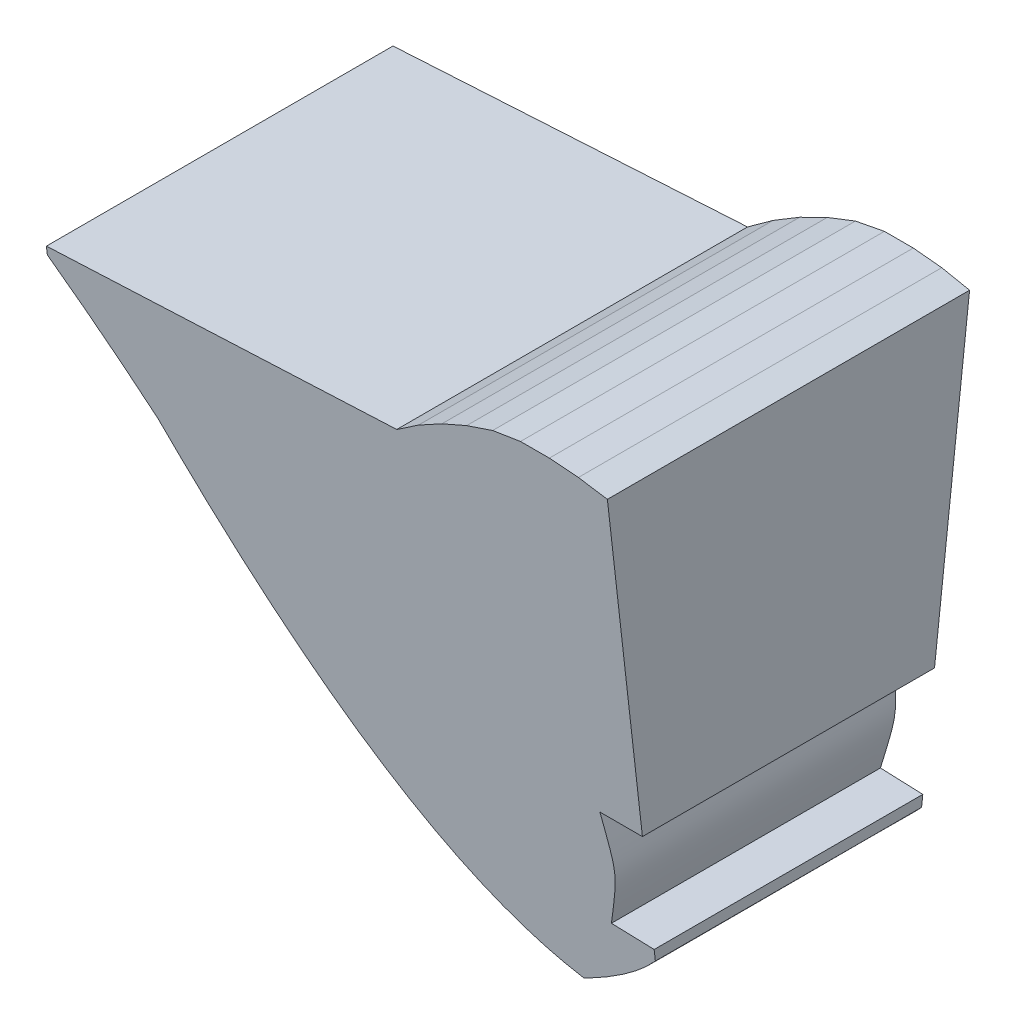
SolidWorks part; units mm, degrees
ref_plane "Alzado" through (0, 0, 0) normal (0, 0, 1) x (1, 0, 0)
ref_plane "Planta" through (0, 0, 0) normal (0, 1, 0) x (1, 0, 0)
ref_plane "Vista lateral" through (0, 0, 0) normal (1, 0, 0) x (0, 0, -1)
sketch "Croquis1" plane through (0, 0, 0) normal (0, 0, 1) x (1, 0, 0)
  line L0 (-8.9818, 12.6082) -> (-23.0359, 11.8716) construction
  line L1 (-8.9818, 12.6082) -> (-23.0359, 11.8716)
  line L2 (-8.9818, 12.6082) -> (-23.0359, 11.8716) construction
  line L4 (-8.9818, 12.6082) -> (-23.0359, 11.8716)
  line L6 (-1.3949, 1.9763) -> (0.3551, 2.2848) construction
  line L7 (-1.3949, 1.9763) -> (0.3551, 2.2848)
  line L8 (0.3551, 2.2848) -> (0.3551, 2.8423) construction
  line L9 (0.3551, 2.2848) -> (0.3551, 3.0015)
  line L10 (0.3551, -2.2848) -> (-1.3949, -2.2237) construction
  line L11 (0.3551, -2.2848) -> (-1.3949, -2.2237)
  line L12 (0.3551, 2.2848) -> (0.3551, -2.2848) construction
  line L13 (0.3551, -2.2848) -> (0.3551, -2.7233)
  line L14 (-8.9818, 12.6082) -> (-6.9949, 10.4774)
  line L15 (-23.0359, 11.5401) -> (-23.0359, 11.8716) construction
  line L16 (-23.0359, 11.5401) -> (-23.0359, 11.8716)
  arc A0 (-18.9452, 7.5409) -> (-23.0359, 11.5401) centre (-69.8841, -40.4718) ccw construction
  arc A1 (-18.9452, 7.5409) -> (-23.0359, 11.5401) centre (-69.8841, -40.4718) ccw
  spline S1 degree 2 poles (-828.7061, 3922.2202) (545.889, -3962.7836) (-262.0834, 3982.5902) knots 0.462185 0.462185 0.462185 0.537731 0.537731 0.537731 weights 1 1 1 only from (-18.9452, 7.5409) to (-2.8466, -5.0591) construction
  spline S2 degree 2 poles (-18.9452, 7.5409) (-10.215, -3.6976) (-2.8466, -5.0591) knots 0.497667 0.497667 0.497667 0.499554 0.499554 0.499554 weights 1 1 1
  spline S3 degree 2 poles (-3804.8689, 1232.5771) (3762.9122, -1369.6643) (-3716.5752, 1504.852) knots 0.462212 0.462212 0.462212 0.537836 0.537836 0.537836 weights 1 1 1 only from (0.3551, 3.0015) to (-6.9949, 10.4774) construction
  spline S4 degree 2 poles (0.3551, 3.0015) (-1.4487, 6.0584) (-6.9949, 10.4774) knots 0.500821 0.500821 0.500821 0.502013 0.502013 0.502013 weights 1 1 1
  spline S5 degree 2 poles (-1.3949, -2.2237) (-0.9075, -0.1237) (-1.3949, 1.9763) knots 0 0 0 1 1 1 weights 1 3.231801 1 construction
  spline S6 degree 2 poles (-1.3949, -2.2237) (-0.9075, -0.1237) (-1.3949, 1.9763) knots 0 0 0 1 1 1 weights 1 3.231801 1
  spline S7 degree 2 poles (-3997.263, 185.0077) (3984.2333, -348.7483) (-3965.0625, 511.2595) knots 0.462205 0.462205 0.462205 0.537778 0.537778 0.537778 weights 1 1 1 only from (-2.8466, -5.0591) to (0.3551, -2.7233) construction
  spline S8 degree 2 poles (-2.8466, -5.0591) (-0.7424, -3.9352) (0.3551, -2.7233) knots 0.498812 0.498812 0.498812 0.499413 0.499413 0.499413 weights 1 1 1
extrude "Saliente-Extruir1" add sketch "Croquis1" along normal mid plane 14.42 contours S2 S8 L13 L11 S6 L7 L9 S4 L14 L1 L16 A1
sketch "Croquis3" plane through (0, 0, 0) normal (0, 0, 1) x (1, 0, 0)
  line L0 (-6.742, 0) -> (0, 0) construction
  line L1 (-1.8181, 2) -> (-1.7771, 2.0103) construction
  line L3 (-1.8181, 2) -> (-0.1689, 2.4155) construction
  line L4 (-1.8181, 2) -> (0.3551, 3.0015)
  line L5 (0.3551, 3.0015) -> (0.3551, 0)
  line L6 (-1.9112, -2.1782) -> (0.3551, -2.2848)
  line L7 (0.3551, -2.2848) -> (0.3551, 0)
  parabola Q0 (-1.9112, -2.1782) -> (-1.8181, 2) focus (-3.3181, 0) apex (-1.3181, 0)
  dimension "D1" = 2
  dimension "D2" = 2
extrude "Cortar-Extruir1" [suppressed] cut sketch "Croquis3" against normal through all both and the other way through all
sketch "Croquis4" plane through (0, 0, 0) normal (0, 0, 1) x (1, 0, 0)
  line L0 (-1.3949, 1.9763) -> (0.3551, 2.2848) construction
  line L1 (-1.3949, 1.9763) -> (0.3551, 2.2848)
  line L2 (0.3551, 2.2848) -> (0.3551, 3.0015) construction
  line L3 (0.3551, 1.9763) -> (0.3551, 2.2848)
  line L4 (-1.3949, 1.9763) -> (0.3551, 1.9763)
  line L5 (0, 0) -> (-3.4665, 0) construction
  dimension "D1" = 0
extrude "Saliente-Extruir2" add sketch "Croquis4" along normal through all and the other way through all
sketch "Croquis7" plane through (0, 0, 0) normal (0, 0, 1) x (1, 0, 0)
  line L0 (0, 0) -> (-13.2475, 1.1183) construction
  line L1 (-14.9286, 14.3063) -> (-13.2475, 1.1183) construction
  line L2 (-13.2475, 1.1183) -> (-7.4174, -4.4688) construction
  line L3 (-13.2475, 1.1183) -> (-8.4034, 6.1732) construction
  line L4 (-14.9286, 14.3063) -> (-14.7, 12.5132) construction
  line L5 (0, 0) -> (-1.3461, -2.2254) construction
  line L6 (-69.8841, 29.5282) -> (-81.9382, 42.5765) construction
  line L7 (-69.8841, 29.5282) -> (-20.9497, 29.5282) construction
  line L8 (-17.8101, 13.1658) -> (-25.5429, 13.1658)
  line L9 (-17.6007, 6.3083) -> (-21.9246, 11.9299) construction
  line L10 (0.3551, -2.5) -> (-2.4497, -2.0473)
  line L11 (-1.3461, -2.2254) -> (-2.0075, -3.6222) construction
  line L12 (-1.3461, -2.2254) -> (-1.4547, -2.8987) construction
  line L13 (-1.3461, -2.2254) -> (-1.2286, -1.4976) construction
  line L14 (0.3551, -2.2848) -> (0.3551, -2.7233) construction
  line L15 (0.3551, -2.2848) -> (-1.3949, -2.2237) construction
  line L16 (-2.0075, -3.6222) -> (-2.6381, -4.9541) construction
  line L17 (-2.6331, -4.9434) -> (-3.7044, -5.5324) construction
  line L18 (-2.6331, -4.9434) -> (-3.2248, -3.867) construction
  line L19 (-2.6331, -4.9434) -> (-2.2174, -6.1341) construction
  line L20 (-4.0838, -4.7637) -> (-2.6213, -4.9448) construction
  line L21 (-4.0838, -4.7637) -> (-0.036, -5.9454) construction
  line L22 (-4.0838, -4.7637) -> (-3.7621, -3.6616) construction
  line L23 (-4.0838, -4.7637) -> (-5.4141, -4.1295) construction
  line L24 (-5.4141, -4.1295) -> (-8.69, -2.5677) construction
  line L25 (-8.69, -2.5677) -> (-6.8421, -3.7725) construction
  line L26 (-8.69, -2.5677) -> (-7.9481, -1.4297) construction
  line L27 (-11.4407, -0.2002) -> (-8.69, -2.5677) construction
  line L28 (-11.4407, -0.2002) -> (-14.8546, 2.738) construction
  line L29 (-14.8546, 2.738) -> (-14.5337, 2.3989) construction
  line L30 (-14.8546, 2.738) -> (-14.6199, 2.9602) construction
  line L31 (-17.6007, 6.3083) -> (-14.8546, 2.738) construction
  line L32 (-8.9818, 12.6082) -> (-23.0359, 11.8716) construction
  line L33 (-8.9818, 12.6082) -> (-23.0359, 11.8716)
  line L34 (-21.9246, 11.9299) -> (-21.9826, 13.0367) construction
  line L35 (-21.9246, 11.9299) -> (-23.4156, 13.0367) construction
  arc A0 (-18.9452, 7.5409) -> (-23.0359, 11.5401) centre (-69.8841, -40.4718) ccw construction
  spline S0 degree 2 poles (-828.7061, 3922.2202) (545.889, -3962.7836) (-262.0834, 3982.5902) knots 0.462185 0.462185 0.462185 0.537731 0.537731 0.537731 weights 1 1 1 only from (-18.9452, 7.5409) to (-2.8466, -5.0591) construction
  spline S1 degree 2 poles (-18.6263, 7.1332) (-10.0803, -3.7225) (-2.8466, -5.0591) knots 0.497702 0.497702 0.497702 0.499554 0.499554 0.499554 weights 1 1 1 construction
  spline S3 degree 2 poles (-3997.263, 185.0077) (3984.2333, -348.7483) (-3965.0625, 511.2595) knots 0.462205 0.462205 0.462205 0.537778 0.537778 0.537778 weights 1 1 1 only from (-2.8466, -5.0591) to (0.3551, -2.7233) construction
  spline S4 degree 2 poles (-2.8466, -5.0591) (-2.7385, -5.0013) (-2.6331, -4.9434) knots 0.498812 0.498812 0.498812 0.498843 0.498843 0.498843 weights 1 1 1
  dimension "D1" = 2.5
  dimension "D2" = 22
  dimension "D3" = 16.17
  dimension "D4" = 54.138
  dimension "D5" = 34.566
  dimension "D6" = 50.413
sketch "Croquis6" plane through (0, 0, 0) normal (1, 0, 0) x (0, 0, -1)
  line L0 (7.21, 12.6082) -> (7.21, 10.4774) construction
  line L1 (7.21, 12.6082) -> (7.21, -5.0591)
  line L2 (-7.21, 12.6082) -> (-7.21, 10.4774) construction
  line L3 (-7.21, 12.6082) -> (-7.21, -5.0591)
  line L4 (-7.21, -5.0591) -> (7.21, -5.0591) construction
  line L5 (-7.21, -5.0591) -> (-5.21, -5.0591)
  line L6 (7.21, 12.6082) -> (5.21, -5.0591)
  line L7 (-7.21, 12.6082) -> (-5.21, -5.0591)
  line L8 (5.21, -5.0591) -> (7.21, -5.0591)
  dimension "D1" = 2
  dimension "D2" = 2
extrude "Cortar-Extruir2" cut sketch "Croquis6" against normal through all and the other way through all
sketch "Croquis8" plane through (0, 0, 0) normal (0, 0, 1) x (1, 0, 0)
  line L0 (-8.9818, 12.6082) -> (-23.0359, 11.8716) construction
  line L1 (-9.7264, 12.5691) -> (0.3551, 14.7092) construction
  line L2 (0.3551, 1.9763) -> (0.3551, 3.0015) construction
  line L3 (0.3551, 3.0015) -> (0.3551, 14.7092)
  line L5 (-8.5414, 12.6312) -> (-7.5693, 13.3119)
  line L6 (-7.5693, 13.3119) -> (-6.5416, 13.9052)
  line L7 (-6.5416, 13.9052) -> (-5.4661, 14.4067)
  line L8 (-5.4661, 14.4067) -> (-4.351, 14.8126)
  line L9 (-4.351, 14.8126) -> (-3.1824, 15.0187)
  line L10 (-3.1824, 15.0187) -> (-1.9957, 15.0187)
  line L11 (-1.9957, 15.0187) -> (-0.8135, 14.9152)
  line L12 (-0.8135, 14.9152) -> (0.3551, 14.7092)
  line L13 (-0.5199, 1.9763) -> (-9.282, 12.9915) construction
  line L14 (-9.282, 12.9915) -> (-9.6919, 13.4229) construction
  line L15 (-9.282, 12.9915) -> (-9.8512, 13.838) construction
  line L16 (-0.5199, 1.9763) -> (-8.0553, 12.9716) construction
  line L17 (-8.0553, 12.9716) -> (-8.7743, 13.9984) construction
  line L18 (-0.5199, 1.9763) -> (-7.0555, 13.6086) construction
  line L19 (0.3551, 1.9763) -> (-1.3949, 1.9763) construction
  line L20 (-7.0555, 13.6086) -> (-7.1957, 13.8514) construction
  line L21 (-0.5199, 1.9763) -> (-6.0039, 14.156) construction
  line L22 (-0.5199, 1.9763) -> (-4.9086, 14.6097) construction
  line L23 (-4.9086, 14.6097) -> (-5.4157, 16.003) construction
  line L24 (-0.5199, 1.9763) -> (-3.7667, 14.9156) construction
  line L25 (-3.7667, 14.9156) -> (-4.0067, 16.2767) construction
  line L26 (-0.5199, 1.9763) -> (-2.589, 15.0187) construction
  line L27 (-2.589, 15.0187) -> (-2.589, 16.5179) construction
  line L28 (-0.5199, 1.9763) -> (-1.4046, 14.967) construction
  line L29 (-1.4046, 14.967) -> (-1.2805, 16.3851) construction
  line L30 (-0.5199, 1.9763) -> (-0.2292, 14.8122) construction
  line L31 (-0.2292, 14.8122) -> (-0.1276, 15.3885) construction
  line L32 (-7.0555, 13.6086) -> (-7.5873, 14.5298) construction
  line L33 (-6.0039, 14.156) -> (-6.4614, 15.1371) construction
  line L34 (-9.7264, 12.5691) -> (-9.7264, 19.4167) construction
  line L35 (-0.2292, 14.8122) -> (0.0596, 16.45) construction
  line L36 (-9.7264, 12.5691) -> (-8.5414, 12.6312)
  spline S0 degree 2 poles (-1851.9698, 781.7085) (1883.9916, -685.7524) (-1911.5868, 588.043) knots 0.476049 0.476049 0.476049 0.529551 0.529551 0.529551 weights 1 1 1 only from (-6.9949, 10.4774) to (0.3551, 3.0015) construction
  spline S1 degree 2 poles (-9.7264, 12.5691) (-1.8611, 6.7573) (0.3551, 3.0015) knots 0.500548 0.500548 0.500548 0.502013 0.502013 0.502013 weights 1 1 1
  point P6 (-8.7235, 13.1193)
  dimension "D1" = 5.039
  dimension "D2" = 95
  dimension "D3" = 80
  dimension "D4" = 70
  dimension "D5" = 55
  dimension "D6" = 60
  dimension "D7" = 65
  dimension "D8" = 90
  dimension "D9" = 100
extrude "Saliente-Extruir3" add sketch "Croquis8" along normal up to surface and the other way up to surface up to face at (-6.8548, 3.8413, 6.2176) other way up to face at (-6.9269, 3.652, -6.1961)
